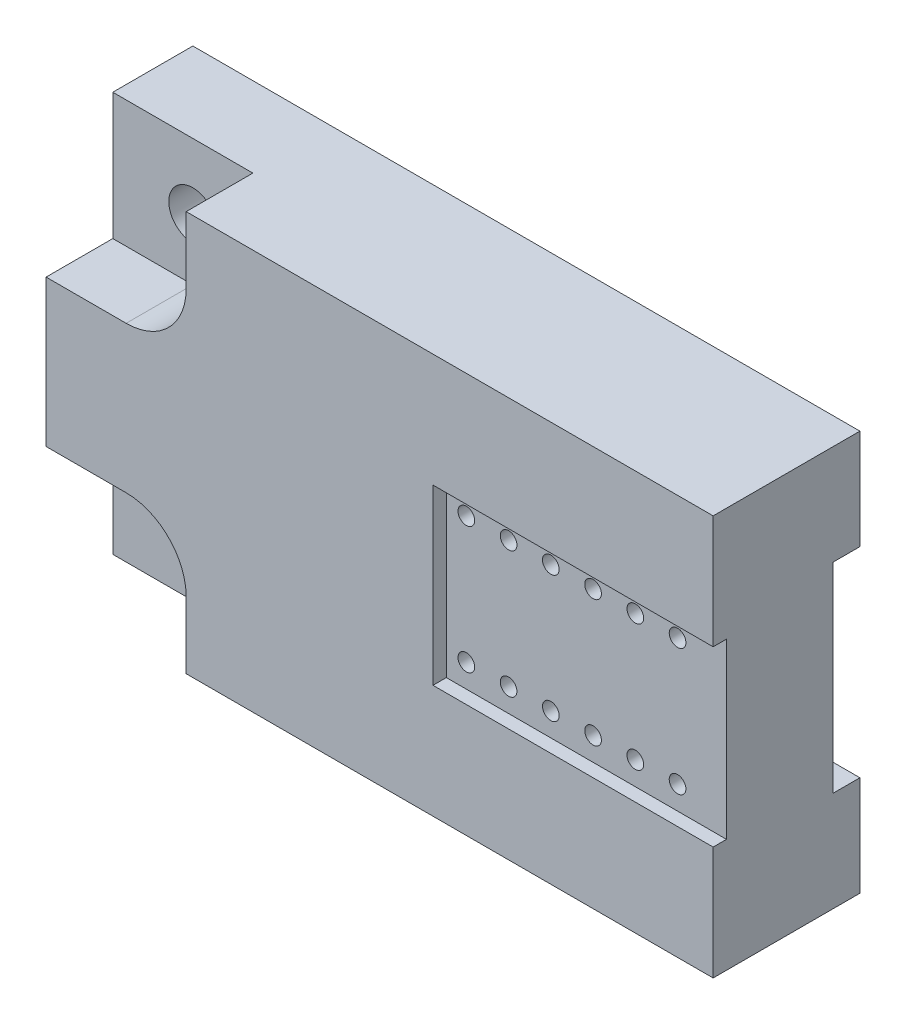
SolidWorks part; units mm, degrees
ref_plane "Ebene vorne" through (0, 0, 0) normal (0, 0, 1) x (1, 0, 0)
ref_plane "Ebene oben" through (0, 0, 0) normal (0, 1, 0) x (1, 0, 0)
ref_plane "Ebene rechts" through (0, 0, 0) normal (1, 0, 0) x (0, 0, -1)
sketch "Skizze1" plane through (0, 0, 0) normal (0, 0, 1) x (1, 0, 0)
  line L1 (0, 0) -> (-100, 0)
  line L2 (0, 0) -> (0, -60)
  line L3 (0, -60) -> (-100, -60)
  line L4 (-100, 0) -> (-100, -60)
  dimension "D1" = 100
  dimension "D2" = 60
extrude "Aufsatz-Linear austragen1" add sketch "Skizze1" along normal blind 12
sketch "Skizze3" plane through (0, 0, 12) normal (0, 0, 1) x (1, 0, 0)
  line L0 (-100, -60) -> (0, -60) construction
  line L1 (-100, 0) -> (-100, -60) construction
  circle A0 centre (-88, -10) radius 3.6
  circle A1 centre (-88, -50) radius 3.6
  dimension "D1" = 7.2
  dimension "D2" = 7.2
  dimension "D3" = 40
  dimension "D4" = 10
  dimension "D5" = 12
  dimension "D6" = 12
extrude "Schnitt-Linear austragen2" cut sketch "Skizze3" against normal blind 20
sketch "Skizze5" plane through (0, 0, 12) normal (0, 0, 1) x (1, 0, 0)
  line L0 (-88, -41) -> (-100, -41)
  line L1 (-100, 0) -> (-100, -60) construction
  line L2 (-79, -50) -> (-79, -60)
  line L3 (-100, -60) -> (0, -60) construction
  line L4 (-79, -10) -> (-79, 0)
  line L8 (-88, -19) -> (-100, -19)
  line L9 (0, 0) -> (-100, 0) construction
  circle A0 centre (-88, -10) radius 9
  circle A1 centre (-88, -50) radius 9
  dimension "D1" = 18
  dimension "D2" = 18
extrude "Aufsatz-Linear austragen2" add sketch "Skizze5" along normal blind 10
sketch "Skizze9" plane through (0, 0, 22) normal (0, 0, 1) x (1, 0, 0)
  line L0 (0, -60) -> (0, 0) construction
  line L1 (0, -17) -> (-42, -17)
  line L2 (0, -17) -> (0, -43)
  line L3 (0, -43) -> (-42, -43)
  line L4 (-42, -17) -> (-42, -43)
  line L5 (0, 0) -> (-79, 0) construction
  dimension "D1" = 26
  dimension "D2" = 42
  dimension "D3" = 17
extrude "Schnitt-Linear austragen6" cut sketch "Skizze9" against normal blind 2
sketch "Skizze10" plane through (0, 0, 0) normal (0, 0, -1) x (-1, 0, 0)
  line L0 (0, -60) -> (0, 0) construction
  line L1 (0, -15) -> (44, -15)
  line L2 (0, -15) -> (0, -45)
  line L3 (0, -45) -> (44, -45)
  line L4 (44, -15) -> (44, -45)
  line L5 (0, 0) -> (100, 0) construction
  dimension "D1" = 15
  dimension "D2" = 30
  dimension "D3" = 44
extrude "Schnitt-Linear austragen7" cut sketch "Skizze10" against normal blind 4
sketch "Skizze11" plane through (0, 0, 20) normal (0, 0, 1) x (1, 0, 0)
  line L2 (0, -17) -> (-42, -17) construction
  line L3 (-42, -17) -> (-42, -43) construction
  circle A20 centre (-39, -20.5) radius 1.25
  circle A21 centre (-39, -39.5) radius 1.25
  circle A22 centre (-32.667, -20.5) radius 1.25
  circle A23 centre (-32.667, -39.5) radius 1.25
  circle A24 centre (-26.334, -20.5) radius 1.25
  circle A25 centre (-26.334, -39.5) radius 1.25
  circle A26 centre (-20.001, -20.5) radius 1.25
  circle A27 centre (-20.001, -39.5) radius 1.25
  circle A28 centre (-13.668, -20.5) radius 1.25
  circle A29 centre (-13.668, -39.5) radius 1.25
  circle A30 centre (-7.335, -20.5) radius 1.25
  circle A31 centre (-7.335, -39.5) radius 1.25
  dimension "D1" = 3.5
  dimension "D2" = 19
  dimension "D4" = 2.5
  dimension "D3" = 3
extrude "Schnitt-Linear austragen8" cut sketch "Skizze11" against normal through all
sketch "Skizze12" plane through (0, 0, 20) normal (0, 0, 1) x (1, 0, 0)
  line L0 (-39, -20.5) -> (-20.001, -39.5)
  line L1 (-20.001, -20.5) -> (-39, -39.5)
  line L4 (-100, -60) -> (-79, -60) construction
  line L5 (-100, 0) -> (-100, -19) construction
  circle A0 centre (-88, -10) radius 3.6 construction
  circle A1 centre (-88, -50) radius 3.6 construction
  point P8 (-29.5005, -30)
  point P9 (0, 0)
  point P16 (0, 0)
  point P17 (0, 0)
  dimension "D2" = 20
  dimension "D3" = 30
  dimension "D1" = 58.4995
  dimension "D4" = 70.4995
